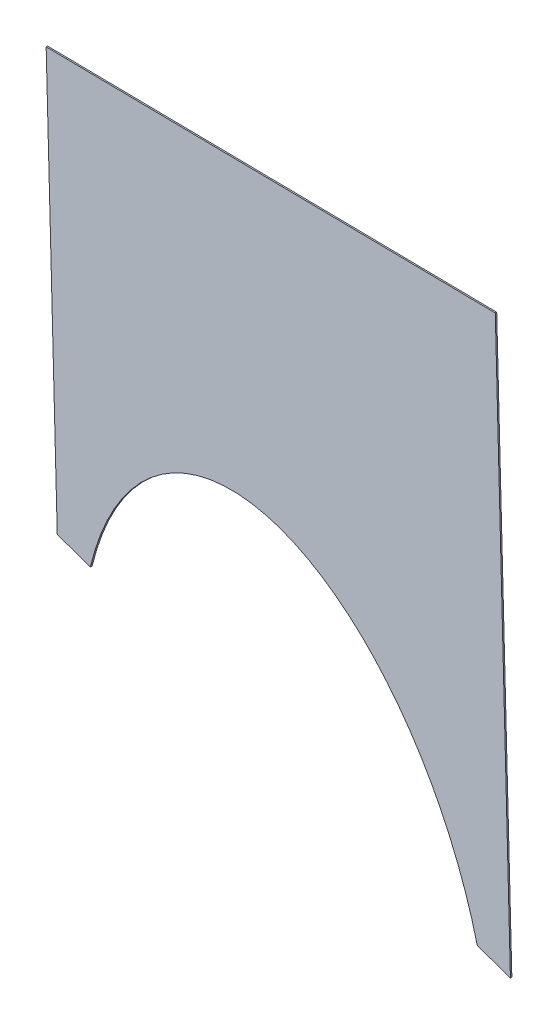
SolidWorks part; units mm, degrees
ref_plane "Front Plane" through (0, 0, 0) normal (0, 0, 1) x (1, 0, 0)
ref_plane "Top Plane" through (0, 0, 0) normal (0, 1, 0) x (1, 0, 0)
ref_plane "Right Plane" through (0, 0, 0) normal (1, 0, 0) x (0, 0, -1)
sketch3d "3DSketch1"
  line L0 (-11.664, 358.2353, 0) -> (644.2645, 533.9085, 181.9498)
  line L1 (644.2645, 533.9085, 181.9498) -> (660.2452, -65.8787, 181.9498)
  line L2 (-11.664, 358.2353, 0) -> (0.0552, -81.6087, 0)
  line L3 (-11.664, 358.2353, 0) -> (-11.664, 358.2353, -527.1567)
  line L4 (0.0552, -81.6087, 0) -> (660.2452, -65.8787, 181.9498)
  dimension "D1" = 703
  dimension "D2" = 600
  dimension "D3" = 440
  dimension "D4" = 105
  dimension "D5" = 103
  dimension "D7" = 90
extrude "Boss-Extrude1" add sketch "3DSketch1" along direction (0, 0, -1) on the side of the normal blind 1.5 contours L0 L1 L4 L2
sketch "Sketch2" plane through (-0.5334, -0.0142, 1.9367) normal (-0.2655, -0.0071, 0.9641) x (0.9641, -0.0019, 0.2655)
  line L0 (0.6105, -81.5954) -> (50.6105, -80.3494)
  line L1 (0.6105, -81.5954) -> (685.3826, -64.5307) construction
  line L2 (685.3826, -64.5307) -> (635.3826, -65.7767)
  line L3 (50.6105, -80.3494) -> (635.3826, -65.7767)
  arc A0 (50.6105, -80.3494) -> (635.3826, -65.7767) centre (345.5674, -176.2245) cw
  line M5 (0.6105, -81.5954) -> (685.3826, -64.5307)
  dimension "D1" = 50
  dimension "D2" = 50
extrude "Cut-Extrude6" cut sketch "Sketch2" against normal blind 11.5 contours A0 M5
sketch "Sketch3" plane through (-0.5334, -0.0142, 1.9367) normal (-0.2655, -0.0071, 0.9641) x (0.9641, -0.0019, 0.2655)
  line L0 (50.6105, -80.3494) -> (50.6105, -106.1987)
  line L1 (50.6105, -106.1987) -> (633.7792, -106.1987)
  line L2 (633.7792, -106.1987) -> (635.3826, -65.7767)
  line L3 (635.3826, -65.7767) -> (592.9234, -33.3377)
  line L4 (592.9234, -33.3377) -> (162.9652, -33.3377)
  line L5 (162.9652, -33.3377) -> (50.6105, -80.3494)
extrude "Cut-Extrude7" cut sketch "Sketch3" against normal blind 11.5
